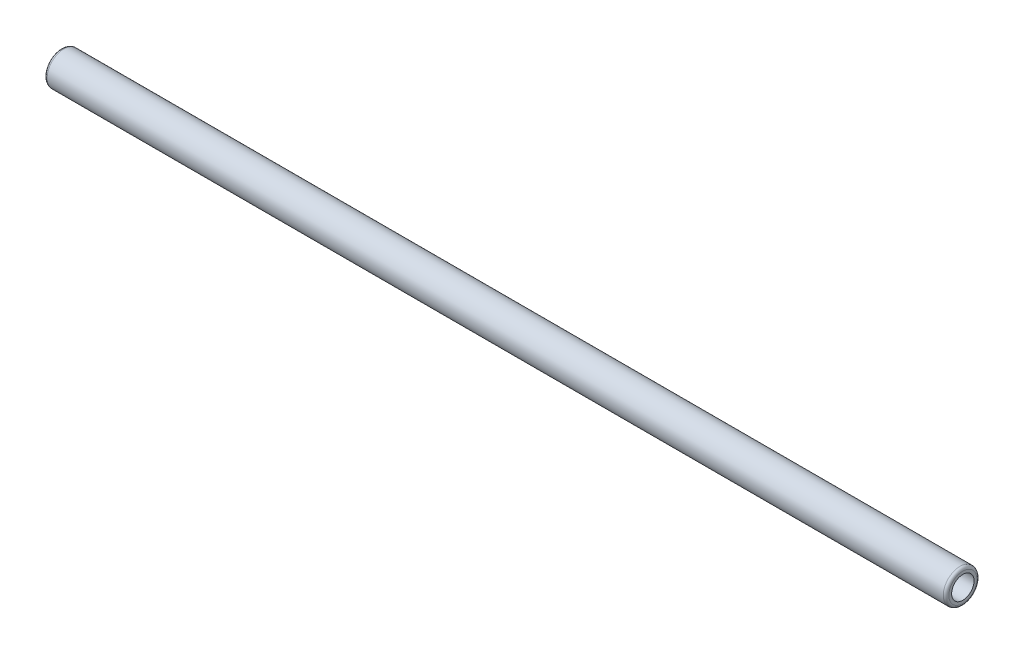
SolidWorks part; units mm, degrees
ref_plane "Спереди" through (0, 0, 0) normal (0, 0, 1) x (1, 0, 0)
ref_plane "Сверху" through (0, 0, 0) normal (0, 1, 0) x (1, 0, 0)
ref_plane "Справа" through (0, 0, 0) normal (1, 0, 0) x (0, 0, -1)
other "Configuration Table"
sketch "Эскиз1" plane through (0, 0, 0) normal (1, 0, 0) x (0, 0, -1)
  circle A0 centre (0, 0) radius 2
  circle A1 centre (0, 0) radius 3
  dimension "D1" = 6
  dimension "D2" = 4
extrude "Бобышка-Вытянуть1" add sketch "Эскиз1" along normal blind 161
fillet "Скругление1" radius 0.5 2 edges at (0, 0, -3) (161, 0, -3)
